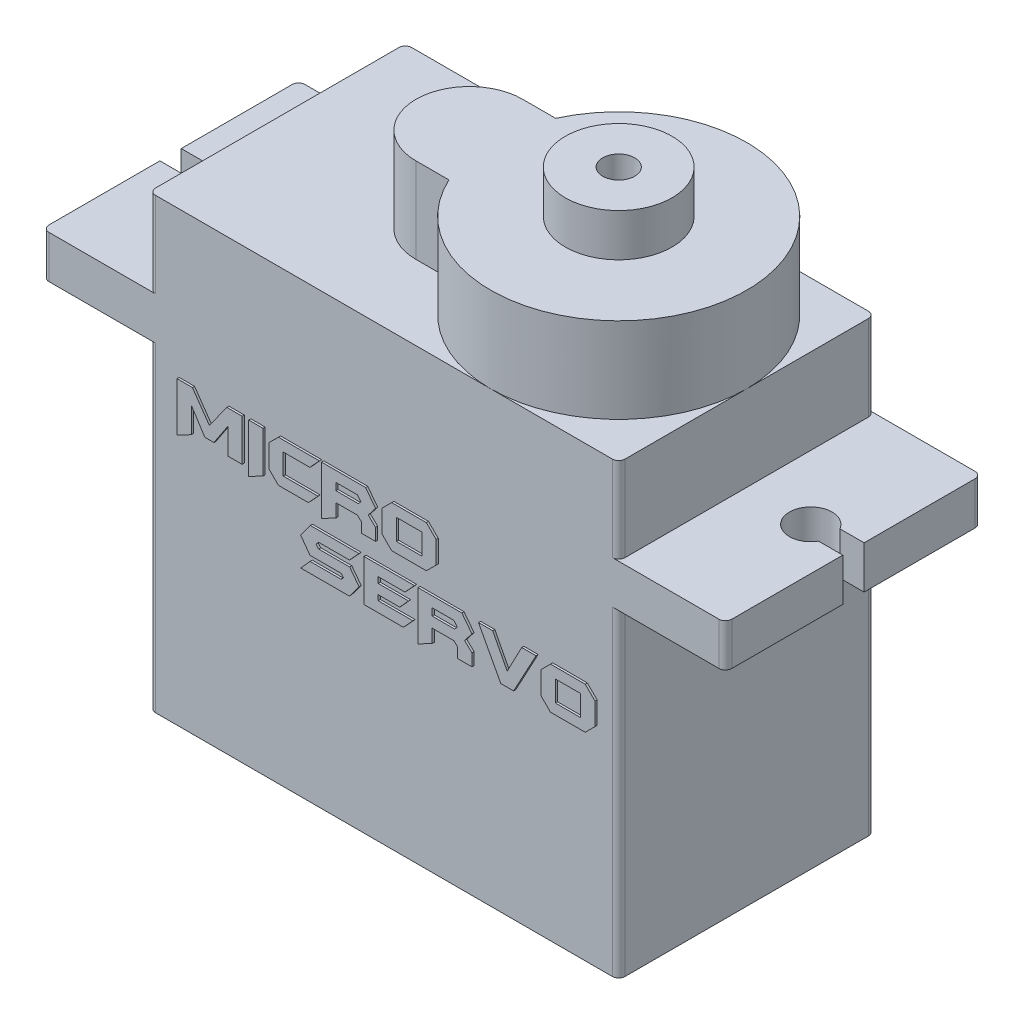
SolidWorks part; units mm, degrees
ref_plane "Front Plane" through (0, 0, 0) normal (0, 0, 1) x (1, 0, 0)
ref_plane "Top Plane" through (0, 0, 0) normal (0, 1, 0) x (1, 0, 0)
ref_plane "Right Plane" through (0, 0, 0) normal (1, 0, 0) x (0, 0, -1)
sketch "Sketch1" plane through (0, 0, 0) normal (0, 1, 0) x (1, 0, 0)
  line L1 (-16, -6) -> (16, -6)
  line L2 (-16, -6) -> (-16, 6)
  line L3 (-16, 6) -> (16, 6)
  line L4 (16, -6) -> (16, 6)
  line L5 (-16, -6) -> (16, 6) construction
  line L6 (-16, 6) -> (16, -6) construction
  point P0 (0, 0)
  dimension "D1" = 32
  dimension "D2" = 12
extrude "Boss-Extrude1" add sketch "Sketch1" along normal blind 2
sketch "Sketch2" plane through (0, 0, 0) normal (0, -1, 0) x (1, 0, 0)
  line L0 (-16, 6) -> (16, 6) construction
  line L1 (-11, -6) -> (11, -6)
  line L2 (-11, -6) -> (-11, 6)
  line L3 (-11, 6) -> (11, 6)
  line L4 (11, -6) -> (11, 6)
  line L5 (-11, -6) -> (11, 6) construction
  line L6 (-11, 6) -> (11, -6) construction
  point P0 (0, 0)
  dimension "D1" = 22
extrude "Boss-Extrude2" add sketch "Sketch2" along normal blind 15
sketch "Sketch3" plane through (0, 2, 0) normal (0, 1, 0) x (1, 0, 0)
  line L0 (16, 6) -> (-16, 6) construction
  line L1 (-11, -6) -> (11, -6)
  line L2 (-11, -6) -> (-11, 6)
  line L3 (-11, 6) -> (11, 6)
  line L4 (11, -6) -> (11, 6)
  line L5 (-11, -6) -> (11, 6) construction
  line L6 (-11, 6) -> (11, -6) construction
  point P0 (0, 0)
  dimension "D1" = 22
extrude "Boss-Extrude3" add sketch "Sketch3" along normal blind 4
sketch "Sketch4" plane through (0, 6, 0) normal (0, 1, 0) x (1, 0, 0)
  line L0 (11, 6) -> (-1, 6)
  line L1 (11, 6) -> (-11, 6) construction
  line L2 (-1, 6) -> (-1, -6)
  line L3 (-11, -6) -> (11, -6) construction
  line L4 (-1, -6) -> (11, 6)
  circle A0 centre (5, 0) radius 6
  dimension "D1" = 12
extrude "Boss-Extrude4" add sketch "Sketch4" along normal blind 4 contours L4 A0 | A0 L4
sketch "Sketch5" plane through (0, 6, 0) normal (0, 1, 0) x (1, 0, 0)
  line L0 (5, 0) -> (-2, 0)
  line L1 (-2, 2.5) -> (-0.4544, 2.5)
  line L2 (-2, -2.5) -> (-0.4544, -2.5)
  circle A0 centre (-2, 0) radius 2.5
  circle A1 centre (5, 0) radius 6 construction
  circle A2 centre (5, 0) radius 6
  dimension "D2" = 5
  dimension "D1" = 7
extrude "Boss-Extrude5" add sketch "Sketch5" along normal blind 4
sketch "Sketch6" plane through (0, 10, 0) normal (0, 1, 0) x (1, 0, 0)
  circle A0 centre (5, 0) radius 2.5
  circle A1 centre (5, 0) radius 0.75
  dimension "D1" = 5
  dimension "D2" = 1.5
extrude "Boss-Extrude6" add sketch "Sketch6" along normal blind 2
sketch "Sketch7" plane through (0, 2, 0) normal (0, 1, 0) x (1, 0, 0)
  line L0 (16, 0) -> (14, 0)
  line L1 (16, -6) -> (16, 6) construction
  line L2 (-16, 0) -> (-14, 0)
  line L3 (-16, 6) -> (-16, -6) construction
  line L5 (18.5, -0.5) -> (13.5, -0.5)
  line L6 (18.5, -0.5) -> (18.5, 0.5)
  line L7 (18.5, 0.5) -> (13.5, 0.5)
  line L8 (13.5, -0.5) -> (13.5, 0.5)
  line L9 (18.5, -0.5) -> (13.5, 0.5) construction
  line L10 (18.5, 0.5) -> (13.5, -0.5) construction
  line L11 (-18.5, -0.5) -> (-13.5, -0.5)
  line L12 (-18.5, -0.5) -> (-18.5, 0.5)
  line L13 (-18.5, 0.5) -> (-13.5, 0.5)
  line L14 (-13.5, -0.5) -> (-13.5, 0.5)
  line L15 (-18.5, -0.5) -> (-13.5, 0.5) construction
  line L16 (-18.5, 0.5) -> (-13.5, -0.5) construction
  circle A0 centre (14, 0) radius 1
  circle A1 centre (-14, 0) radius 1
  dimension "D2" = 2
  dimension "D4" = 2
  dimension "D1" = 2
  dimension "D3" = 2
  dimension "D5" = 1
  dimension "D6" = 5
  dimension "D7" = 1
  dimension "D8" = 5
extrude "Cut-Extrude1" cut sketch "Sketch7" against normal through all contours L7 L8 L5 L6 | A0 | L13 L14 L11 L12 | A1
fillet "Fillet1" radius 0.3 12 edges at (-16, 1, -6) (-16, 1, 6) (16, 1, -6) (16, 1, 6)
sketch "Sketch8" plane through (0, 0, 6) normal (0, 0, 1) x (1, 0, 0)
  text T0 "<b>MICRO</b>" font "BatmanForeverAlternate" height in points 8
  text T1 "<b>SERVO</b>" font "BatmanForeverAlternate" height in points 8
extrude "Boss-Extrude7" add sketch "Sketch8" along normal blind 0.1
